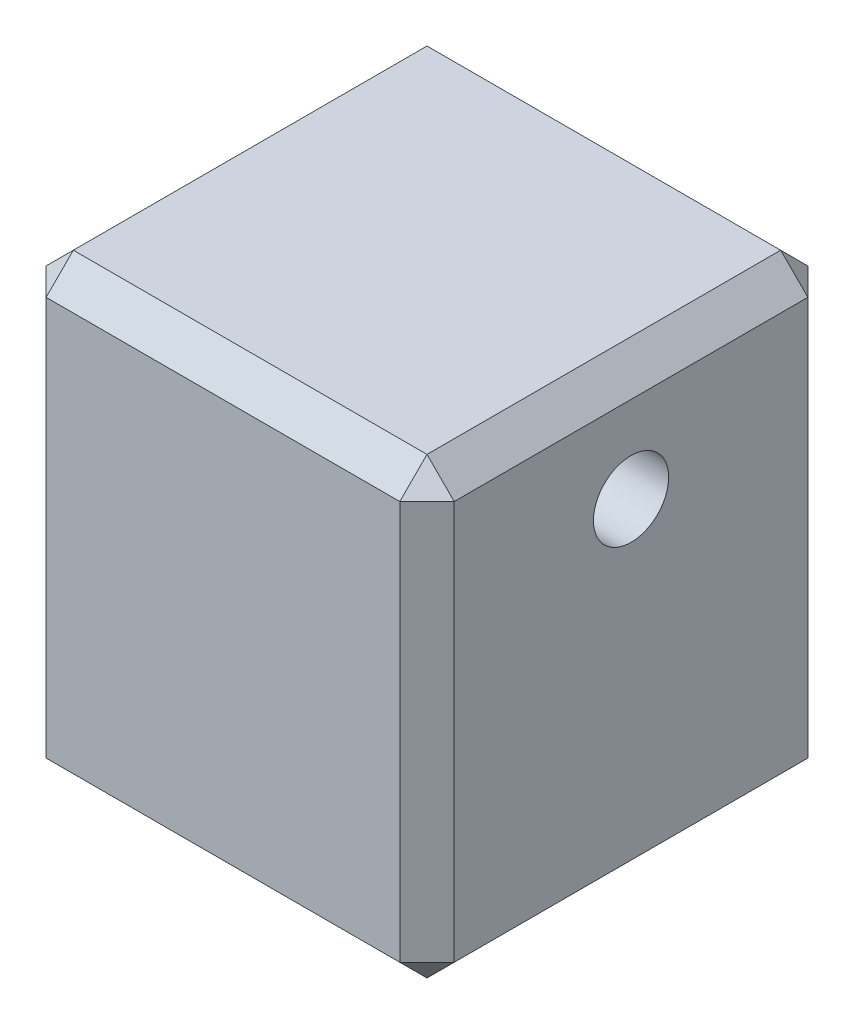
SolidWorks part; units mm, degrees
ref_plane "前视基准面" through (0, 0, 0) normal (0, 0, 1) x (1, 0, 0)
ref_plane "上视基准面" through (0, 0, 0) normal (0, 1, 0) x (1, 0, 0)
ref_plane "右视基准面" through (0, 0, 0) normal (1, 0, 0) x (0, 0, -1)
sketch "Sketch1" plane through (0, 0, 0) normal (0, 1, 0) x (1, 0, 0)
  line L1 (-22.5, 22.5) -> (22.5, 22.5)
  line L2 (-22.5, 22.5) -> (-22.5, -22.5)
  line L3 (-22.5, -22.5) -> (22.5, -22.5)
  line L4 (22.5, 22.5) -> (22.5, -22.5)
  line L5 (-22.5, 22.5) -> (22.5, -22.5) construction
  line L6 (-22.5, -22.5) -> (22.5, 22.5) construction
  point P0 (0, 0)
  dimension "D1" = 45
  dimension "D2" = 45
extrude "Boss-Extrude1" add sketch "Sketch1" along normal blind 50
sketch "Sketch2" plane through (0, 0, -22.5) normal (0, 0, -1) x (-1, 0, 0)
  circle A0 centre (0, 12.5) radius 4.15
  dimension "D1" = 8.3
  dimension "D2" = 12.5
extrude "Cut-Extrude1" cut sketch "Sketch2" against normal blind 30
sketch "Sketch3" plane through (22.5, 0, 0) normal (-1, 0, 0) x (0, 0, 1)
  line L1 (-22.5, 50) -> (22.5, 50) construction
  circle A0 centre (0, 37.5) radius 4.15
  dimension "D1" = 8.3
  dimension "D2" = 12.5
extrude "Cut-Extrude2" cut sketch "Sketch3" along normal blind 30
chamfer "Chamfer1" distance 3 angle 45 12 edges at (0, 0, -22.5) (22.5, 0, 0) (22.5, 25, 22.5) (0, 0, 22.5) (-22.5, 25, -22.5) (-22.5, 0, 0) (-22.5, 25, 22.5) (0, 50, 22.5) (-22.5, 50, 0) (0, 50, -22.5) (22.5, 50, 0) (22.5, 25, -22.5)
